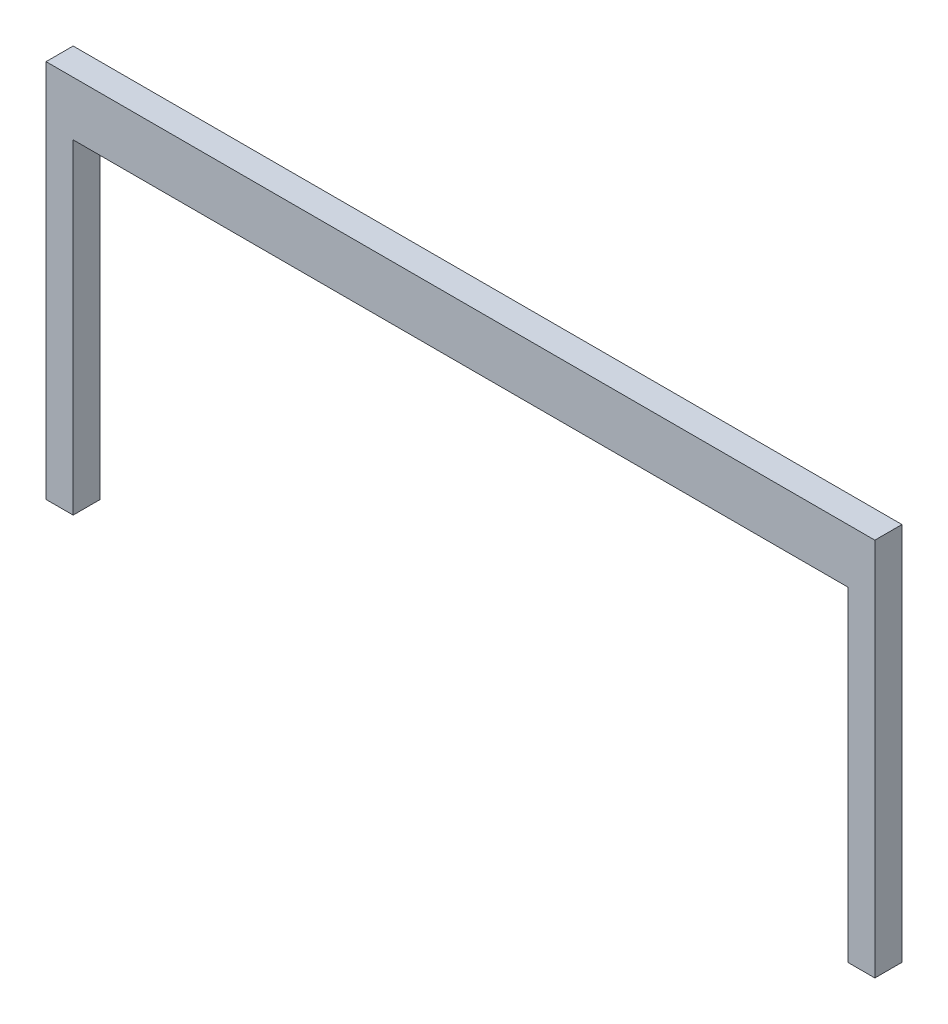
SolidWorks part; units mm, degrees
ref_plane "前视基准面" through (0, 0, 0) normal (0, 0, 1) x (1, 0, 0)
ref_plane "上视基准面" through (0, 0, 0) normal (0, 1, 0) x (1, 0, 0)
ref_plane "右视基准面" through (0, 0, 0) normal (1, 0, 0) x (0, 0, -1)
sketch "草图1" plane through (0, 0, 0) normal (0, 0, 1) x (1, 0, 0)
  line L0 (71.5, 30.9089) -> (-71.5, 30.9089)
  line L1 (-71.5, 30.9089) -> (-71.5, -29.0911)
  line L2 (-71.5, -29.0911) -> (-76.5, -29.0911)
  line L3 (-76.5, -29.0911) -> (-76.5, 40.9089)
  line L4 (-76.5, 40.9089) -> (76.5, 40.9089)
  line L5 (0, 35.0468) -> (0, 30.9089) construction
  line L6 (0, 30.9089) -> (0, -21.5049) construction
  line L7 (76.5, -29.0911) -> (76.5, 40.9089)
  line L8 (71.5, -29.0911) -> (76.5, -29.0911)
  line L9 (71.5, 30.9089) -> (71.5, -29.0911)
  line L10 (0, 40.9089) -> (0, 35.0468) construction
  line L11 (0, 35.0468) -> (0, 30.9089) construction
  dimension "D1" = 10
  dimension "D2" = 70
  dimension "D3" = 5
  dimension "D4" = 153
extrude "凸台-拉伸1" add sketch "草图1" along normal blind 5
